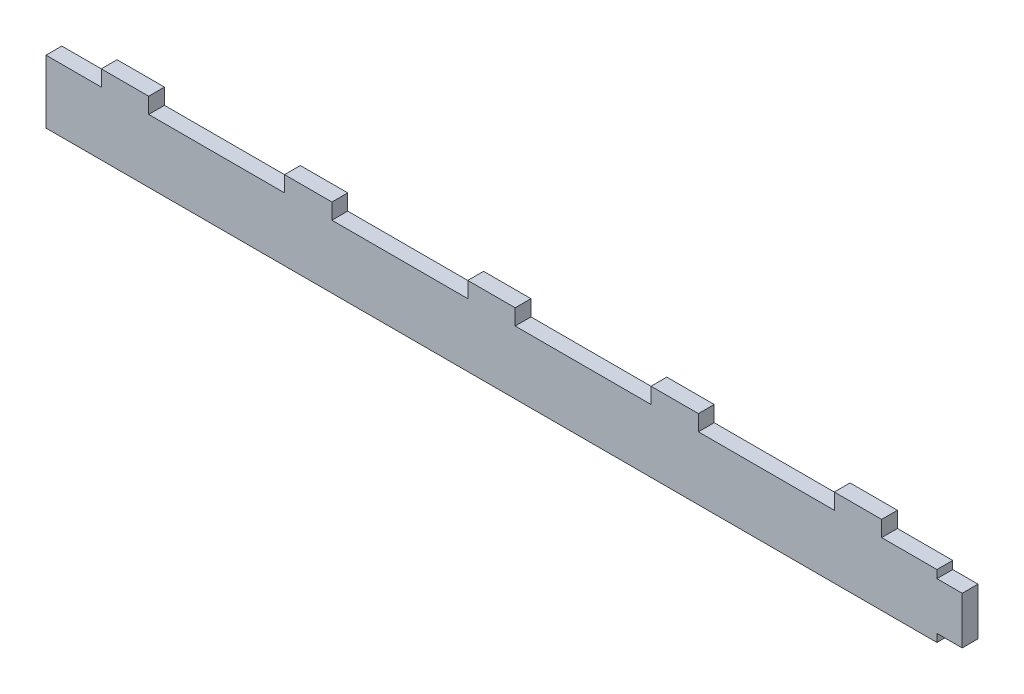
SolidWorks part; units mm, degrees
material "PVC 0.007 plastifié"
ref_plane "Plan de face" through (0, 0, 0) normal (0, 0, 1) x (1, 0, 0)
ref_plane "Plan de dessus" through (0, 0, 0) normal (0, 1, 0) x (1, 0, 0)
ref_plane "Plan de droite" through (0, 0, 0) normal (1, 0, 0) x (0, 0, -1)
sketch "Esquisse1" plane through (0, 0, 0) normal (0, 0, 1) x (1, 0, 0)
  line L1 (-109.7956, 67.9416) -> (180.2044, 67.9416)
  line L2 (-109.7956, 67.9416) -> (-109.7956, 42.9416)
  line L3 (-109.7956, 42.9416) -> (180.2044, 42.9416)
  line L4 (180.2044, 67.9416) -> (180.2044, 42.9416)
  line L5 (-109.7956, 67.9416) -> (-92.2956, 67.9416)
  line L6 (-109.7956, 67.9416) -> (-109.7956, 62.9416)
  line L7 (-109.7956, 62.9416) -> (-92.2956, 62.9416)
  line L8 (-92.2956, 67.9416) -> (-92.2956, 62.9416)
  line L9 (-77.2956, 67.9416) -> (-34.2956, 67.9416)
  line L10 (-77.2956, 67.9416) -> (-77.2956, 62.9416)
  line L11 (-77.2956, 62.9416) -> (-34.2956, 62.9416)
  line L12 (-34.2956, 67.9416) -> (-34.2956, 62.9416)
  line L13 (-19.2956, 67.9416) -> (23.7044, 67.9416)
  line L14 (-19.2956, 67.9416) -> (-19.2956, 62.9416)
  line L15 (-19.2956, 62.9416) -> (23.7044, 62.9416)
  line L16 (23.7044, 67.9416) -> (23.7044, 62.9416)
  line L17 (38.7044, 67.9416) -> (81.7044, 67.9416)
  line L18 (38.7044, 67.9416) -> (38.7044, 62.9416)
  line L19 (38.7044, 62.9416) -> (81.7044, 62.9416)
  line L20 (81.7044, 67.9416) -> (81.7044, 62.9416)
  line L21 (96.7044, 67.9416) -> (139.7044, 67.9416)
  line L22 (96.7044, 67.9416) -> (96.7044, 62.9416)
  line L23 (96.7044, 62.9416) -> (139.7044, 62.9416)
  line L24 (139.7044, 67.9416) -> (139.7044, 62.9416)
  line L25 (154.7044, 67.9416) -> (180.2044, 67.9416)
  line L26 (154.7044, 67.9416) -> (154.7044, 62.9416)
  line L27 (154.7044, 62.9416) -> (180.2044, 62.9416)
  line L28 (180.2044, 67.9416) -> (180.2044, 62.9416)
  line L29 (180.2044, 62.9416) -> (172.2044, 62.9416)
  line L30 (180.2044, 62.9416) -> (180.2044, 60.4416)
  line L31 (180.2044, 60.4416) -> (172.2044, 60.4416)
  line L32 (172.2044, 62.9416) -> (172.2044, 60.4416)
  line L33 (180.2044, 42.9416) -> (172.2044, 42.9416)
  line L34 (180.2044, 42.9416) -> (180.2044, 45.4416)
  line L35 (180.2044, 45.4416) -> (172.2044, 45.4416)
  line L36 (172.2044, 42.9416) -> (172.2044, 45.4416)
  dimension "D1" = 290
  dimension "D2" = 25
  dimension "D3" = 17.5
  dimension "D4" = 5
  dimension "D5" = 5
  dimension "D6" = 15
  dimension "D7" = 43
  dimension "D8" = 15
  dimension "D9" = 43
  dimension "D10" = 5
  dimension "D11" = 15
  dimension "D12" = 43
  dimension "D13" = 5
  dimension "D14" = 15
  dimension "D15" = 43
  dimension "D16" = 5
  dimension "D17" = 15
  dimension "D18" = 5
  dimension "D19" = 15
  dimension "D20" = 2.5
  dimension "D21" = 8
  dimension "D22" = 8
extrude "Boss.-Extru.2" add sketch "Esquisse1" along normal blind 5 contours L3 L36 L35 L4 L31 L32 L27 L26 L1 L24 L23 L22 L20 L19 L18 L16 L15 L14 L12 L11 L10 L8 L7 L2
